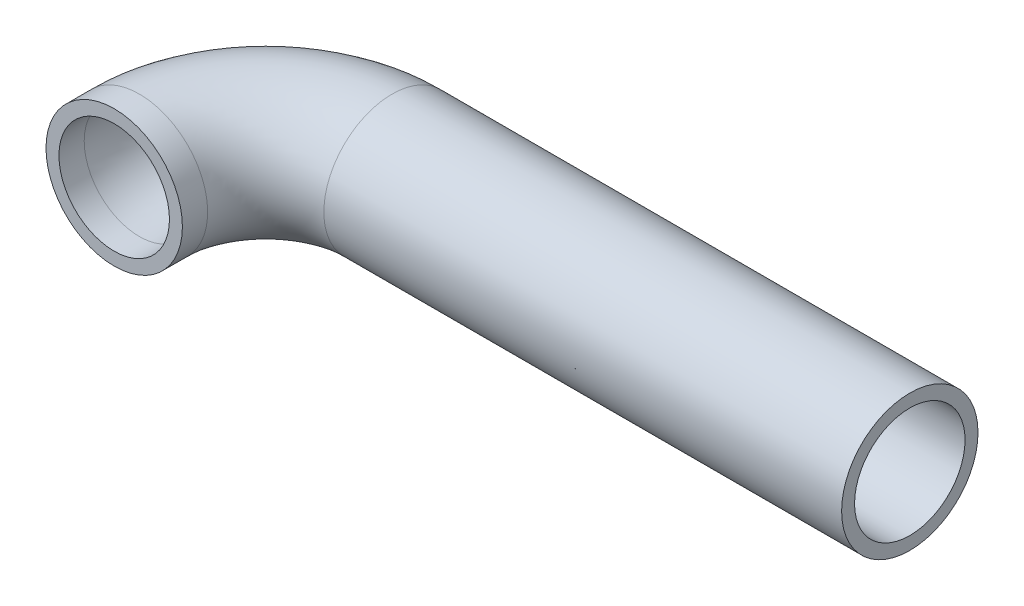
SolidWorks part; units mm, degrees
ref_plane "Front Plane" through (0, 0, 0) normal (0, 0, 1) x (1, 0, 0)
ref_plane "Top Plane" through (0, 0, 0) normal (0, 1, 0) x (1, 0, 0)
ref_plane "Right Plane" through (0, 0, 0) normal (1, 0, 0) x (0, 0, -1)
sketch "Sketch1" plane through (0, 0, 0) normal (0, 0, 1) x (1, 0, 0)
  circle A0 centre (0, 0) radius 5.5562
  circle A1 centre (0, 0) radius 6.858
  dimension "D1" = 11.1125
  dimension "D2" = 13.716
sketch "Sketch2" plane through (0, 0, 0) normal (0, 1, 0) x (1, 0, 0)
  line L0 (0, 0) -> (0, 2.54)
  line L1 (12.7, 15.24) -> (64.77, 15.24)
  arc A0 (0, 2.54) -> (12.7, 15.24) centre (12.7, 2.54) cw
  point P6 (58.0858, 50.8)
  dimension "D2" = 12.7
  dimension "D1" = 2.54
  dimension "D3" = 52.07
sweep "Sweep1" add profiles "Sketch1" path "Sketch2"
